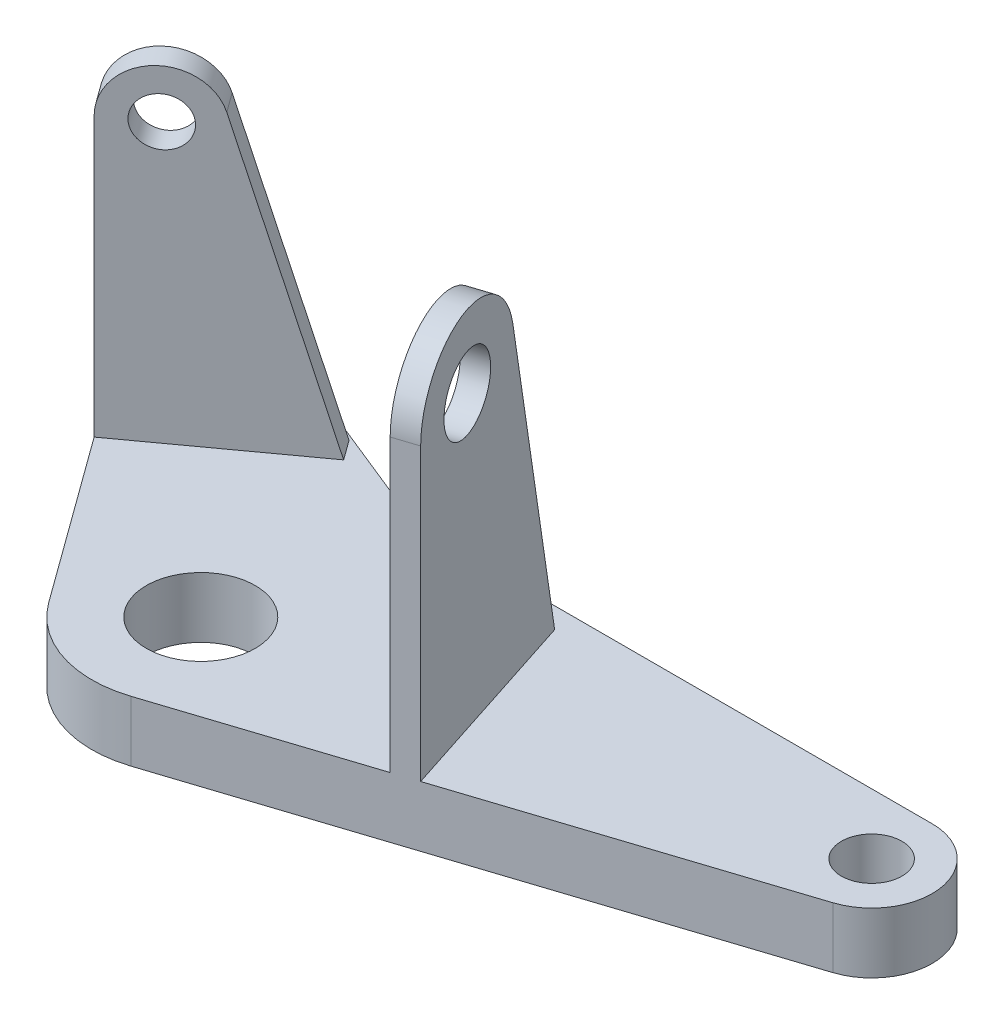
SolidWorks part; units mm, degrees
ref_plane "Front Plane" through (0, 0, 0) normal (0, 0, 1) x (1, 0, 0)
ref_plane "Top Plane" through (0, 0, 0) normal (0, 1, 0) x (1, 0, 0)
ref_plane "Right Plane" through (0, 0, 0) normal (1, 0, 0) x (0, 0, -1)
sketch "Sketch1" plane through (0, 0, 0) normal (0, 1, 0) x (1, 0, 0)
  line L0 (5.5623, -17.119) -> (93.0902, 11.3205)
  line L1 (90, 30.8311) -> (12.8607, 30.8311)
  line L2 (-2.8728, 33.8894) -> (-45.7524, 51.2138)
  line L3 (-52.8541, 42.124) -> (-14.5623, -10.5801)
  circle A0 centre (0, 0) radius 9
  arc A1 (-45.7524, 51.2138) -> (-52.8541, 42.124) centre (-48, 45.6507) ccw
  arc A2 (93.0902, 11.3205) -> (90, 30.8311) centre (90, 20.8311) ccw
  arc A3 (5.5623, -17.119) -> (-14.5623, -10.5801) centre (0, 0) cw
  arc A4 (12.8607, 30.8311) -> (-2.8728, 33.8894) centre (12.8607, 72.8311) cw
  circle A5 centre (-48, 45.6507) radius 3
  circle A6 centre (90, 20.8311) radius 5
  dimension "D1" = 6
  dimension "D2" = 10
  dimension "D3" = 18
  dimension "D4" = 42
  dimension "D6" = 6
  dimension "D7" = 10
  dimension "D8" = 18
  dimension "D5" = 18
  dimension "D9" = 22
  dimension "D10" = 54
  dimension "D11" = 48
  dimension "D12" = 90
extrude "Boss-Extrude1" add sketch "Sketch1" along normal blind 10
ref_plane "Plane1" through (0, 0, 0) normal (-0.9511, 0, 0.309) x (0, -1, 0)
ref_plane "Plane2" through (32.3359, 0, -10.5066) normal (-0.9511, 0, 0.309) x (0, -1, 0)
sketch "l" plane through (32.3359, 0, -10.5066) normal (-0.9511, 0, 0.309) x (0, -1, 0)
  line L3 (-10, 18) -> (-58, 18)
  line L4 (-60.4949, -5.7378) -> (-10, -16.4708)
  line L5 (-10, -56.3951) -> (-10, 5.5623) construction
  line L6 (-10, 18) -> (-10, 5.5623) construction
  line L7 (-10, -16.4708) -> (-10, 18)
  arc A2 (-58, 18) -> (-60.4949, -5.7378) centre (-58, 6) ccw
  circle A3 centre (-58, 6) radius 6
  dimension "D3" = 12
  dimension "D4" = 12
  dimension "D1" = 12
  dimension "D2" = 48
extrude "Boss-Extrude2" add sketch "l" against normal blind 4
sketch "Sketch4" plane through (0, 10, 0) normal (0, 1, 0) x (1, 0, 0)
  line L0 (-34.547, 16.9264) -> (11.1791, 50.1484) construction
  line L2 (-52.8541, 42.124) -> (-14.5623, -10.5801) construction
  dimension "D1" = 34
ref_plane "Plane5" through (0, 0, 0) normal (-0.5878, 0, -0.809) x (0, -1, 0)
ref_plane "Plane6" through (-19.9847, 0, -27.5066) normal (-0.5878, 0, -0.809) x (0, -1, 0)
sketch "Sketch6" plane through (-19.9847, 0, -27.5066) normal (-0.5878, 0, -0.809) x (0, -1, 0)
  line L0 (-10, 18) -> (-56, 18)
  line L1 (-58.2051, 2.3099) -> (-10, -11.5127)
  line L2 (-10, 200018) -> (-10, -200038.5206) construction
  line L3 (-10, -11.5127) -> (-10, 18)
  arc A0 (-56, 18) -> (-58.2051, 2.3099) centre (-56, 10) ccw
  circle A1 centre (-56, 10) radius 4
  dimension "D1" = 8
  dimension "D2" = 8
  dimension "D3" = 16
  dimension "D4" = 46
extrude "Boss-Extrude3" add sketch "Sketch6" along normal blind 4
